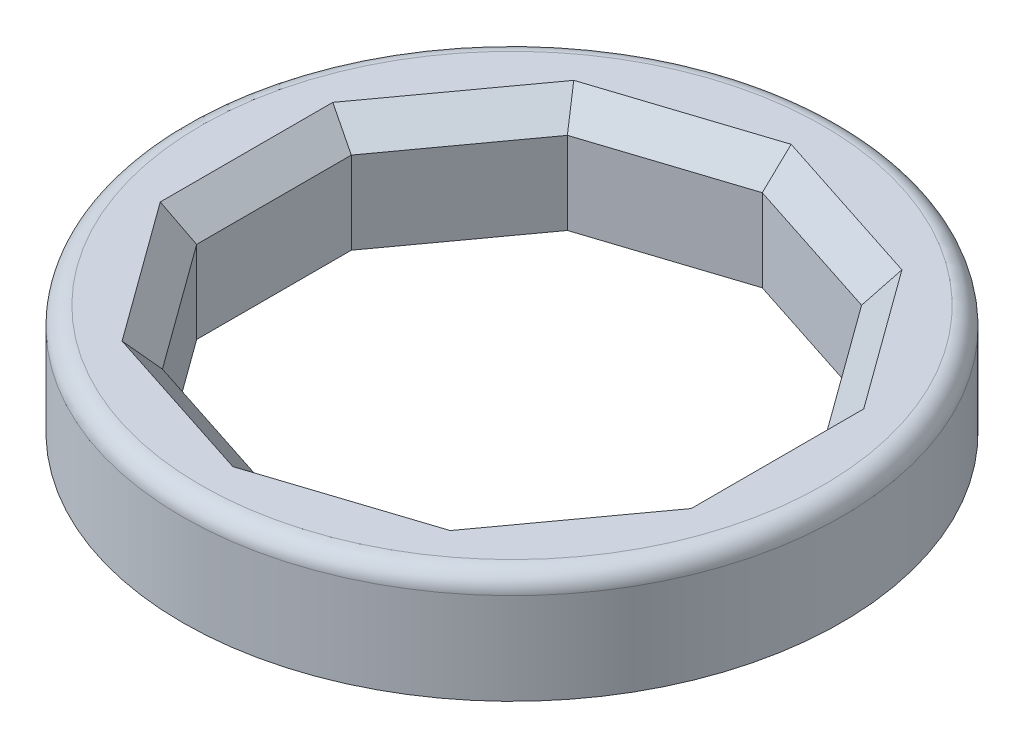
SolidWorks part; units mm, degrees
ref_plane "Front Plane" through (0, 0, 0) normal (0, 0, 1) x (1, 0, 0)
ref_plane "Top Plane" through (0, 0, 0) normal (0, 1, 0) x (1, 0, 0)
ref_plane "Right Plane" through (0, 0, 0) normal (1, 0, 0) x (0, 0, -1)
sketch "Sketch1" plane through (0, 0, 0) normal (0, 1, 0) x (1, 0, 0)
  line L1 (16.0689, 22.1169) -> (0, 27.338)
  line L2 (0, 27.338) -> (-16.0689, 22.1169)
  line L3 (-16.0689, 22.1169) -> (-26, 8.4479)
  line L4 (-26, 8.4479) -> (-26, -8.4479)
  line L5 (-26, -8.4479) -> (-16.0689, -22.1169)
  line L6 (-16.0689, -22.1169) -> (0, -27.338)
  line L7 (0, -27.338) -> (16.0689, -22.1169)
  line L8 (16.0689, -22.1169) -> (26, -8.4479)
  line L9 (26, -8.4479) -> (26, 8.4479)
  line L10 (26, 8.4479) -> (16.0689, 22.1169)
  circle A0 centre (0, 0) radius 36
  circle A1 centre (0, 0) radius 26 construction
  dimension "D1" = 72
  dimension "D2" = 10
extrude "Boss-Extrude1" add sketch "Sketch1" along normal blind 12
fillet "Fillet1" radius 2 1 edges at (0, 12, 36)
chamfer "Chamfer1" distance 3 angle 45 10 edges at (-8.0344, 12, 24.7275) (8.0344, 12, 24.7275) (21.0344, 12, 15.2824) (26, 12, 0) (21.0344, 12, -15.2824) (8.0344, 12, -24.7275) (-8.0344, 12, -24.7275) (-21.0344, 12, -15.2824) (-26, 12, 0) (-21.0344, 12, 15.2824)
